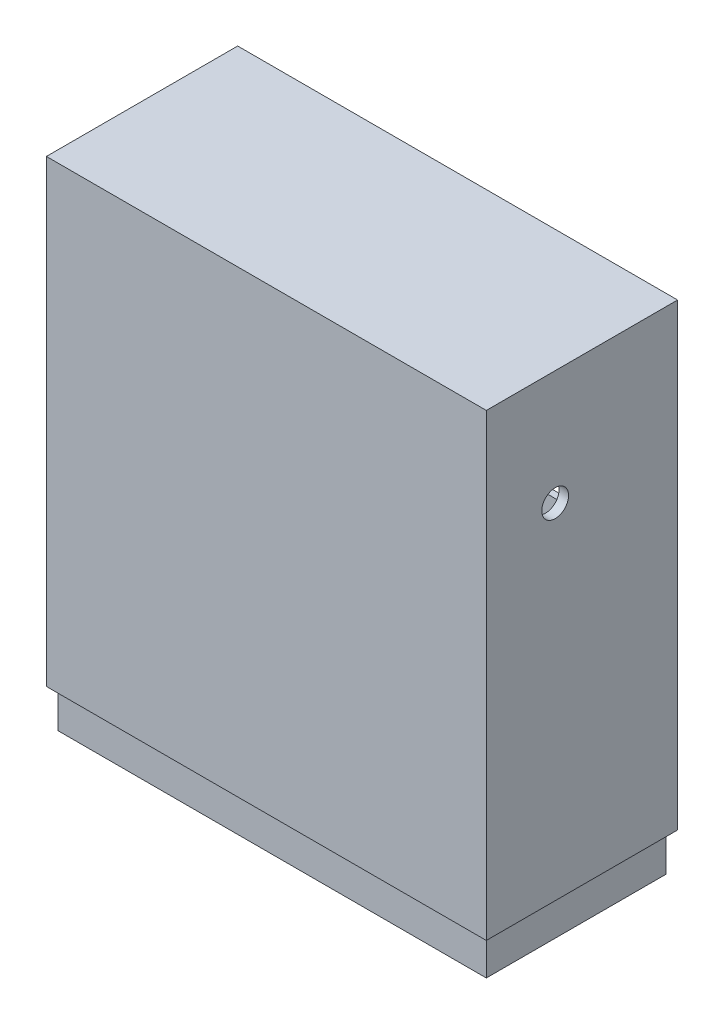
SolidWorks part; units mm, degrees
ref_plane "前视基准面" through (0, 0, 0) normal (0, 0, 1) x (1, 0, 0)
ref_plane "上视基准面" through (0, 0, 0) normal (0, 1, 0) x (1, 0, 0)
ref_plane "右视基准面" through (0, 0, 0) normal (1, 0, 0) x (0, 0, -1)
sketch "草图1" plane through (0, 0, 0) normal (0, 1, 0) x (1, 0, 0)
  line L1 (-57.5, 25) -> (57.5, 25)
  line L2 (-57.5, 25) -> (-57.5, -25)
  line L3 (-57.5, -25) -> (57.5, -25)
  line L4 (57.5, 25) -> (57.5, -25)
  line L5 (-57.5, 25) -> (57.5, -25) construction
  line L6 (-57.5, -25) -> (57.5, 25) construction
  point P0 (0, 0)
  dimension "D1" = 115
  dimension "D2" = 50
extrude "凸台-拉伸1" add sketch "草图1" along normal blind 120 contours L1 L4 L3 L2
sketch "草图4" plane through (0, 0, -25) normal (0, 0, -1) x (-1, 0, 0)
  line L0 (57.5, 120) -> (57.5, 0) construction
  line L1 (-43, 106.5561) -> (43, 106.5561)
  line L2 (-43, 106.5561) -> (-43, 62.5561)
  line L3 (-43, 62.5561) -> (43, 62.5561)
  line L4 (43, 106.5561) -> (43, 62.5561)
  line L5 (-43, 106.5561) -> (43, 62.5561) construction
  line L6 (-43, 62.5561) -> (43, 106.5561) construction
  point P0 (-18.6654, 80.1416)
  point P1 (0, 84.5561)
  dimension "D1" = 86
  dimension "D2" = 44
  dimension "D3" = 57.5
extrude "切除-拉伸3" cut sketch "草图4" against normal blind 28
sketch "草图5" plane through (0, 0, -25) normal (0, 0, -1) x (-1, 0, 0)
  line L2 (-43, 106.5561) -> (43, 62.5561) construction
  line L3 (-43, 62.5561) -> (43, 106.5561) construction
sketch "草图6" plane through (0, 0, -25) normal (0, 0, -1) x (-1, 0, 0)
  line L0 (-43, 106.5561) -> (43, 62.5561) construction
  line L1 (-51, 115.0561) -> (51, 115.0561)
  line L2 (-51, 115.0561) -> (-51, 54.0561)
  line L3 (-51, 54.0561) -> (51, 54.0561)
  line L4 (51, 115.0561) -> (51, 54.0561)
  line L5 (-51, 115.0561) -> (51, 54.0561) construction
  line L6 (-51, 54.0561) -> (51, 115.0561) construction
  point P0 (0, 84.5561)
  dimension "D1" = 102
  dimension "D2" = 61
extrude "切除-拉伸4" cut sketch "草图6" against normal blind 1.8
sketch "草图8" plane through (0, 0, 0) normal (0, -1, 0) x (1, 0, 0)
  line L1 (-56, 23.5) -> (56, 23.5)
  line L2 (-56, 23.5) -> (-56, -23.5)
  line L3 (-56, -23.5) -> (56, -23.5)
  line L4 (56, 23.5) -> (56, -23.5)
  dimension "D1" = 23.5
  dimension "D2" = 23.5
  dimension "D3" = 56
  dimension "D4" = 56
extrude "凸台-拉伸3" add sketch "草图8" along normal blind 10
sketch "草图10" plane through (0, -10, 0) normal (0, -1, 0) x (1, 0, 0)
  line L1 (-55, 22.5) -> (55, 22.5)
  line L2 (-55, 22.5) -> (-55, -21.5)
  line L3 (-55, -21.5) -> (55, -21.5)
  line L4 (55, 22.5) -> (55, -21.5)
  dimension "D1" = 21.5
  dimension "D2" = 22.5
  dimension "D3" = 55
  dimension "D4" = 55
extrude "切除-拉伸5" cut sketch "草图10" against normal blind 127
sketch "草图11" plane through (57.5, 0, 0) normal (1, 0, 0) x (0, 0, -1)
  line L1 (25, 120) -> (-25, 120) construction
  line L2 (-25, 120) -> (-25, 0) construction
  circle A0 centre (-7, 90) radius 3.5
  dimension "D1" = 30
  dimension "D2" = 18
extrude "切除-拉伸6" cut sketch "草图11" against normal blind 10
